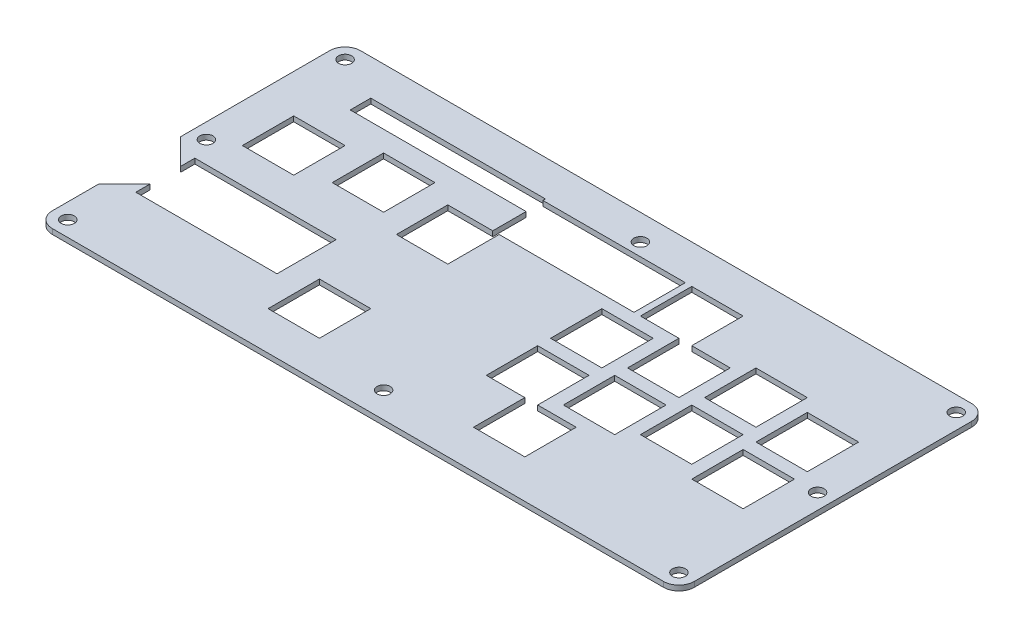
SolidWorks part; units mm, degrees
ref_plane "前视基准面" through (0, 0, 0) normal (0, 0, 1) x (1, 0, 0)
ref_plane "上视基准面" through (0, 0, 0) normal (0, 1, 0) x (1, 0, 0)
ref_plane "右视基准面" through (0, 0, 0) normal (1, 0, 0) x (0, 0, -1)
sketch "草图1" plane through (0, 0, 0) normal (0, 1, 0) x (1, 0, 0)
  line L0 (15.7557, 65.5232) -> (15.7557, 123.5232)
  line L1 (21.7557, 129.5232) -> (259.7557, 129.5232)
  line L2 (265.7557, 123.5232) -> (265.7557, 15.5232)
  line L3 (259.7557, 9.5232) -> (21.7557, 9.5232)
  line L4 (15.7557, 15.5232) -> (15.7557, 33.5232)
  line L5 (25.7557, 43.5232) -> (25.7557, 38.0232)
  line L6 (25.7557, 38.0232) -> (80.7557, 38.0232)
  line L7 (80.7557, 38.0232) -> (80.7557, 61.0232)
  line L8 (80.7557, 61.0232) -> (25.7557, 61.0232)
  line L9 (25.7557, 61.0232) -> (25.7557, 55.5232)
  line L10 (25.7557, 55.5232) -> (15.7557, 65.5232)
  line L11 (25.7557, 43.5232) -> (15.7557, 33.5232)
  line L12 (107.7557, 107.5232) -> (39.7557, 107.5232)
  line L13 (39.7557, 107.5232) -> (39.7557, 115.5232)
  line L14 (39.7557, 115.5232) -> (107.7557, 115.5232)
  line L15 (107.7557, 115.5232) -> (107.7557, 114.5232)
  line L16 (60.7557, 99.5232) -> (80.7557, 99.5232)
  line L17 (80.7557, 99.5232) -> (80.7557, 79.5232)
  line L18 (80.7557, 79.5232) -> (60.7557, 79.5232)
  line L19 (60.7557, 79.5232) -> (60.7557, 99.5232)
  line L20 (110.7557, 94.5232) -> (110.7557, 74.5232)
  line L21 (110.7557, 74.5232) -> (90.7557, 74.5232)
  line L22 (90.7557, 74.5232) -> (90.7557, 94.5232)
  line L23 (90.7557, 94.5232) -> (108.2557, 94.5232)
  line L24 (90.7557, 44.5232) -> (110.7557, 44.5232)
  line L25 (110.7557, 44.5232) -> (110.7557, 24.5232)
  line L26 (110.7557, 24.5232) -> (90.7557, 24.5232)
  line L27 (90.7557, 24.5232) -> (90.7557, 44.5232)
  line L28 (30.7557, 94.5232) -> (50.7557, 94.5232)
  line L29 (50.7557, 94.5232) -> (50.7557, 74.5232)
  line L30 (50.7557, 74.5232) -> (30.7557, 74.5232)
  line L31 (30.7557, 74.5232) -> (30.7557, 94.5232)
  line L32 (180.7557, 94.5232) -> (165.7557, 94.5232)
  line L33 (165.7557, 94.5232) -> (165.7557, 114.5232)
  line L34 (165.7557, 114.5232) -> (185.7557, 114.5232)
  line L35 (185.7557, 114.5232) -> (185.7557, 94.5232)
  line L36 (155.7557, 89.5232) -> (175.7557, 89.5232)
  line L37 (175.7557, 89.5232) -> (175.7557, 69.5232)
  line L38 (175.7557, 69.5232) -> (155.7557, 69.5232)
  line L39 (155.7557, 69.5232) -> (155.7557, 89.5232)
  line L40 (185.7557, 94.5232) -> (200.7557, 94.5232)
  line L41 (200.7557, 94.5232) -> (200.7557, 74.5232)
  line L42 (200.7557, 74.5232) -> (180.7557, 74.5232)
  line L43 (180.7557, 74.5232) -> (180.7557, 94.5232)
  line L44 (205.7557, 99.5232) -> (225.7557, 99.5232)
  line L45 (225.7557, 99.5232) -> (225.7557, 79.5232)
  line L46 (225.7557, 79.5232) -> (205.7557, 79.5232)
  line L47 (205.7557, 79.5232) -> (205.7557, 99.5232)
  line L48 (230.7557, 94.5232) -> (250.7557, 94.5232)
  line L49 (250.7557, 94.5232) -> (250.7557, 74.5232)
  line L50 (250.7557, 74.5232) -> (230.7557, 74.5232)
  line L51 (230.7557, 74.5232) -> (230.7557, 94.5232)
  line L52 (170.7557, 44.5232) -> (155.7557, 44.5232)
  line L53 (155.7557, 44.5232) -> (155.7557, 64.5232)
  line L54 (155.7557, 64.5232) -> (175.7557, 64.5232)
  line L55 (175.7557, 64.5232) -> (175.7557, 44.5232)
  line L56 (180.7557, 69.5232) -> (200.7557, 69.5232)
  line L57 (200.7557, 69.5232) -> (200.7557, 49.5232)
  line L58 (200.7557, 49.5232) -> (180.7557, 49.5232)
  line L59 (180.7557, 49.5232) -> (180.7557, 69.5232)
  line L60 (205.7557, 74.5232) -> (225.7557, 74.5232)
  line L61 (225.7557, 74.5232) -> (225.7557, 54.5232)
  line L62 (225.7557, 54.5232) -> (205.7557, 54.5232)
  line L63 (205.7557, 54.5232) -> (205.7557, 74.5232)
  line L64 (230.7557, 69.5232) -> (250.7557, 69.5232)
  line L65 (250.7557, 69.5232) -> (250.7557, 49.5232)
  line L66 (250.7557, 49.5232) -> (230.7557, 49.5232)
  line L67 (230.7557, 49.5232) -> (230.7557, 69.5232)
  line L68 (175.7557, 44.5232) -> (190.7557, 44.5232)
  line L69 (190.7557, 44.5232) -> (190.7557, 24.5232)
  line L70 (190.7557, 24.5232) -> (170.7557, 24.5232)
  line L71 (170.7557, 24.5232) -> (170.7557, 44.5232)
  line L72 (108.2557, 94.5232) -> (108.2557, 107.5232)
  line L73 (163.2557, 114.5232) -> (163.2557, 94.5232)
  line L74 (108.2557, 114.5232) -> (163.2557, 114.5232)
  line L75 (163.2557, 94.5232) -> (110.7557, 94.5232)
  line L76 (108.2557, 114.5232) -> (107.7557, 114.5232)
  line L77 (107.7557, 107.5232) -> (108.2557, 107.5232)
  arc A0 (21.7557, 129.5232) -> (15.7557, 123.5232) centre (21.7557, 123.5232) ccw
  arc A1 (265.7557, 123.5232) -> (259.7557, 129.5232) centre (259.7557, 123.5232) ccw
  arc A2 (259.7557, 9.5232) -> (265.7557, 15.5232) centre (259.7557, 15.5232) ccw
  arc A3 (15.7557, 15.5232) -> (21.7557, 9.5232) centre (21.7557, 15.5232) ccw
  circle A4 centre (21.7557, 123.5232) radius 2.55
  circle A5 centre (259.7557, 123.5232) radius 2.55
  circle A6 centre (140.7557, 119.5232) radius 2.55
  circle A7 centre (21.7557, 15.5232) radius 2.55
  circle A8 centre (259.7557, 15.5232) radius 2.55
  circle A9 centre (140.7557, 19.5232) radius 2.55
  circle A10 centre (259.7557, 69.5232) radius 2.55
  circle A11 centre (21.7557, 69.5232) radius 2.55
extrude "凸台-拉伸1" add sketch "草图1" along normal blind 2
